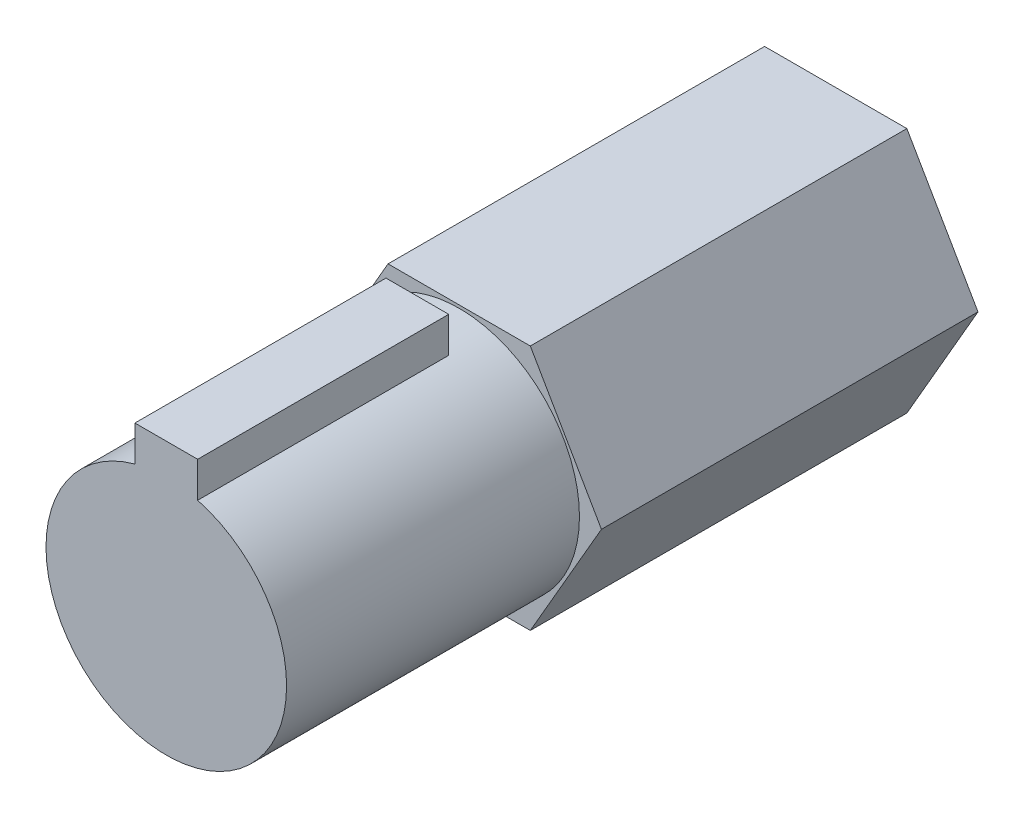
SolidWorks part; units mm, degrees
ref_plane "Front Plane" through (0, 0, 0) normal (0, 0, 1) x (1, 0, 0)
ref_plane "Top Plane" through (0, 0, 0) normal (0, 1, 0) x (1, 0, 0)
ref_plane "Right Plane" through (0, 0, 0) normal (1, 0, 0) x (0, 0, -1)
sketch "Sketch1" plane through (0, 0, 0) normal (0, 0, 1) x (1, 0, 0)
  line L0 (3.4, 0) -> (1.7, 2.9445)
  line L1 (1.7, 2.9445) -> (-1.7, 2.9445)
  line L2 (-1.7, 2.9445) -> (-3.4, 0)
  line L3 (-3.4, 0) -> (-1.7, -2.9445)
  line L4 (-1.7, -2.9445) -> (1.7, -2.9445)
  line L5 (1.7, -2.9445) -> (3.4, 0)
  circle A0 centre (0, 0) radius 3.4 construction
  point P8 (0, 0)
extrude "Boss-Extrude1" add sketch "Sketch1" along normal blind 9 contours L0 L1 L2 L3 L4 L5
sketch "Sketch2" plane through (0, 0, 9) normal (0, 0, 1) x (1, 0, 0)
  circle A0 centre (0, 0) radius 2.875
  dimension "D1" = 5.75
extrude "Boss-Extrude2" add sketch "Sketch2" along normal blind 7
sketch "Sketch3" plane through (0, 0, 16) normal (0, 0, 1) x (1, 0, 0)
  line L0 (-0.75, 3.625) -> (0.75, 3.625)
  line L1 (-0.75, 3.625) -> (-0.75, 2.125)
  line L2 (-0.75, 2.125) -> (0.75, 2.125)
  line L3 (0.75, 3.625) -> (0.75, 2.125)
  line L4 (-0.75, 3.625) -> (0.75, 2.125) construction
  line L5 (-0.75, 2.125) -> (0.75, 3.625) construction
  circle A0 centre (0, 0) radius 2.875 construction
  point P0 (0, 2.875)
  point P5 (0, 2.875)
  point P9 (0, 0)
  point P10 (0, 0)
  point P11 (0, 0)
extrude "Boss-Extrude3" add sketch "Sketch3" against normal blind 6
